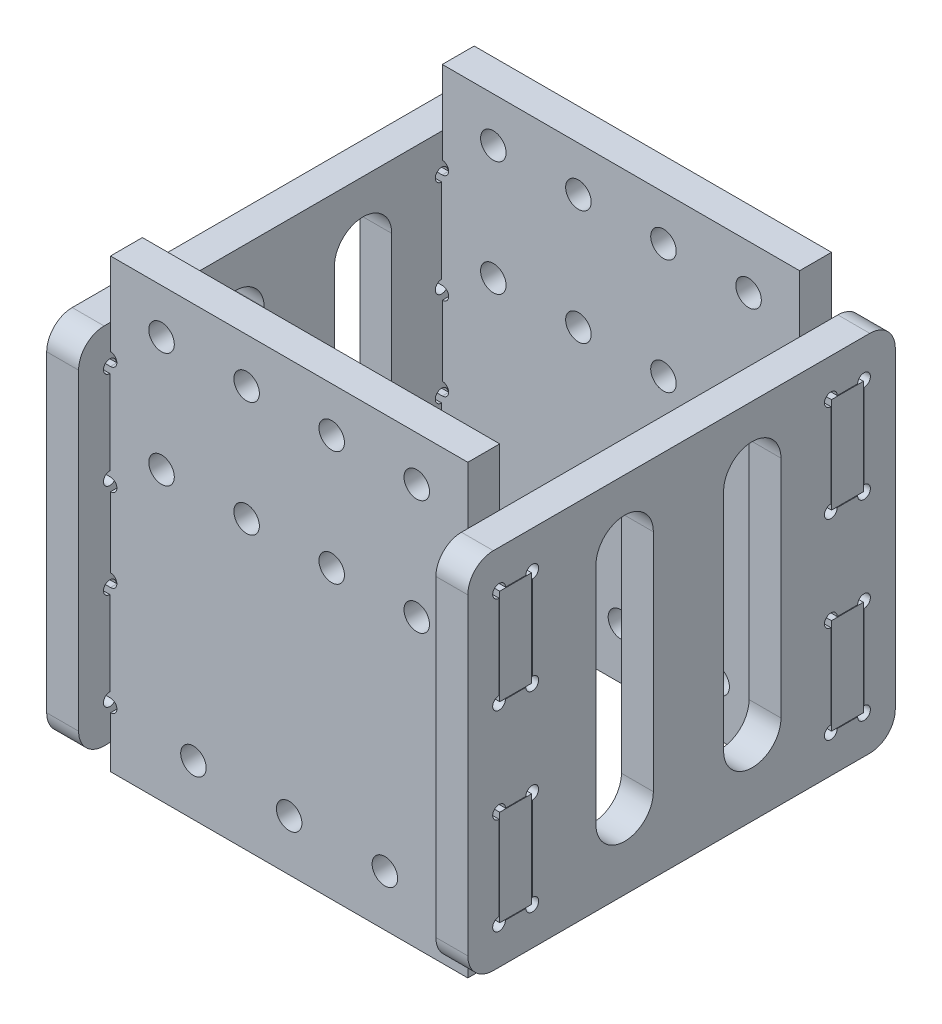
SolidWorks part; units mm, degrees
material "Thornel Mat VMA"
ref_plane "前视基准面" through (0, 0, 0) normal (0, 0, 1) x (1, 0, 0)
ref_plane "上视基准面" through (0, 0, 0) normal (0, 1, 0) x (1, 0, 0)
ref_plane "右视基准面" through (0, 0, 0) normal (1, 0, 0) x (0, 0, -1)
other "Configuration Table"
sketch "草图1" plane through (0, 0, 0) normal (0, 0, 1) x (1, 0, 0)
  line L5 (28, 35) -> (-28, 35)
  line L6 (28, 35) -> (28, 22)
  line L7 (28, -35) -> (-28, -35)
  line L8 (-28, 35) -> (-28, 22)
  line L9 (28, 35) -> (-28, -35) construction
  line L10 (28, -35) -> (-28, 35) construction
  line L11 (-28, 20) -> (-33, 20)
  line L13 (-28, 5) -> (-33, 5)
  line L14 (-33, 20) -> (-33, 5)
  line L15 (-28, 3) -> (-28, -8)
  line L16 (-28, -25) -> (-33, -25)
  line L17 (-33, -10) -> (-33, -25)
  line L18 (-28, -10) -> (-33, -10)
  line L20 (-28, -27) -> (-28, -35)
  line L21 (0, -55) -> (0, 55) construction
  line L22 (28, -25) -> (33, -25)
  line L23 (33, -10) -> (33, -25)
  line L24 (28, -10) -> (33, -10)
  line L25 (28, 5) -> (33, 5)
  line L26 (33, 20) -> (33, 5)
  line L27 (28, 20) -> (33, 20)
  line L28 (28, -25) -> (28, -35)
  line L29 (28, 3) -> (28, -8)
  circle A0 centre (-20, 28) radius 2
  circle A1 centre (-6.6667, 28) radius 2
  circle A2 centre (6.6667, 28) radius 2
  circle A3 centre (20, 28) radius 2
  circle A4 centre (-6.6667, 10) radius 2
  circle A5 centre (6.6667, 10) radius 2
  circle A6 centre (20, 10) radius 2
  circle A7 centre (-20, 10) radius 2
  circle A8 centre (-15, -27) radius 2
  circle A9 centre (0, -27) radius 2
  circle A10 centre (15, -27) radius 2
  arc A11 (-28, 3) -> (-28, 5) centre (-28, 4) ccw
  arc A12 (-28, 20) -> (-28, 22) centre (-28, 21) ccw
  arc A13 (-28, -27) -> (-28, -25) centre (-28, -26) ccw
  arc A14 (-28, -10) -> (-28, -8) centre (-28, -9) ccw
  arc A15 (28, -27) -> (28, -25) centre (28, -26) cw
  arc A16 (28, -10) -> (28, -8) centre (28, -9) cw
  arc A17 (28, 3) -> (28, 5) centre (28, 4) cw
  arc A18 (28, 20) -> (28, 22) centre (28, 21) cw
  point P0 (0, 0)
  dimension "D3" = 4
  dimension "D4" = 8
  dimension "D5" = 7
  dimension "D8" = 8
  dimension "D9" = 18
  dimension "D10" = 40
  dimension "D11" = 4
  dimension "D12" = 8
  dimension "D14" = 15
  dimension "D18" = 2
  dimension "D19" = 2
  dimension "D1" = 56
  dimension "D2" = 70
  dimension "D15" = 5
  dimension "D16" = 15
  dimension "D17" = 15
  dimension "D6" = 4
  dimension "D7" = 2
  dimension "D13" = 3
  dimension "D20" = 2
extrude "凸台-拉伸1" add sketch "草图1" along normal blind 5 contours L27 A18 L6 L5 L8 A12 L11 L14 L13 A11 L15 A14 L18 L17 L16 A13 L20 L7 L28 A15 L22 L23 L24 A16 L29 A17 L25 L26 A0 A1 A2 A3 A4 A5 A6 A7 A8 A9 A10
pattern_linear "阵列(线性)1" count 2 spacing 52 along (0, 0, -1) of bodies 106
sketch "草图2" plane through (-33, 0, 0) normal (-1, 0, 0) x (0, 0, 1)
  line L0 (-52.1, 19.1) -> (-52.1, 5.9)
  line L1 (-51.1, 4.9) -> (-47.9, 4.9)
  line L2 (-46.9, 5.9) -> (-46.9, 19.1)
  line L3 (-47.9, 20.1) -> (-51.1, 20.1)
  line L4 (-52, 20) -> (-52, 5)
  line L5 (-52, 5) -> (-47, 5)
  line L6 (-47, 5) -> (-47, 20)
  line L7 (-47, 20) -> (-52, 20)
  line L8 (-52, 20) -> (-52, 5) construction
  line L9 (-52, 5) -> (-47, 5) construction
  line L10 (-47, 5) -> (-47, 20) construction
  line L11 (-47, 20) -> (-52, 20) construction
  line L12 (-52.1, 4.9) -> (-46.9, 4.9) construction
  line L13 (-46.9, 4.9) -> (-46.9, 20.1) construction
  line L14 (-52.1, 20.1) -> (-52.1, 4.9) construction
  line L15 (-46.9, 20.1) -> (-52.1, 20.1) construction
  line L16 (-52, 35) -> (-52, 22) construction
  line L17 (-57, 26) -> (10, 26)
  line L18 (-57, 26) -> (-57, -31)
  line L19 (-57, -31) -> (10, -31)
  line L20 (10, 26) -> (10, -31)
  line L21 (5, 20) -> (5, 5) construction
  line L22 (-47, -25) -> (-52, -25) construction
  line L23 (-0.1, 19.1) -> (-0.1, 5.9)
  line L24 (0.9, 4.9) -> (4.1, 4.9)
  line L25 (5.1, 5.9) -> (5.1, 19.1)
  line L26 (4.1, 20.1) -> (0.9, 20.1)
  line L27 (0, 20) -> (0, 5) construction
  line L28 (0, 5) -> (5, 5) construction
  line L29 (5, 5) -> (5, 20) construction
  line L30 (5, 20) -> (0, 20) construction
  line L31 (-0.1, -10.9) -> (-0.1, -24.1)
  line L32 (0.9, -25.1) -> (4.1, -25.1)
  line L33 (5.1, -24.1) -> (5.1, -10.9)
  line L34 (4.1, -9.9) -> (0.9, -9.9)
  line L35 (0, -10) -> (0, -25) construction
  line L36 (0, -25) -> (5, -25) construction
  line L37 (5, -25) -> (5, -10) construction
  line L38 (5, -10) -> (0, -10) construction
  line L39 (-52.1, -10.9) -> (-52.1, -24.1)
  line L40 (-51.1, -25.1) -> (-47.9, -25.1)
  line L41 (-46.9, -24.1) -> (-46.9, -10.9)
  line L42 (-47.9, -9.9) -> (-51.1, -9.9)
  line L43 (-52, -10) -> (-52, -25) construction
  line L44 (-52, -25) -> (-47, -25) construction
  line L45 (-47, -25) -> (-47, -10) construction
  line L46 (-47, -10) -> (-52, -10) construction
  arc A0 (-46.9, 19.1) -> (-47.9, 20.1) centre (-46.9, 20.1) ccw
  arc A1 (-51.1, 20.1) -> (-52.1, 19.1) centre (-52.1, 20.1) ccw
  arc A2 (-52.1, 5.9) -> (-51.1, 4.9) centre (-52.1, 4.9) ccw
  arc A3 (-47.9, 4.9) -> (-46.9, 5.9) centre (-46.9, 4.9) ccw
  arc A4 (5.1, 19.1) -> (4.1, 20.1) centre (5.1, 20.1) ccw
  arc A5 (0.9, 20.1) -> (-0.1, 19.1) centre (-0.1, 20.1) ccw
  arc A6 (-0.1, 5.9) -> (0.9, 4.9) centre (-0.1, 4.9) ccw
  arc A7 (4.1, 4.9) -> (5.1, 5.9) centre (5.1, 4.9) ccw
  arc A8 (5.1, -10.9) -> (4.1, -9.9) centre (5.1, -9.9) ccw
  arc A9 (0.9, -9.9) -> (-0.1, -10.9) centre (-0.1, -9.9) ccw
  arc A10 (-0.1, -24.1) -> (0.9, -25.1) centre (-0.1, -25.1) ccw
  arc A11 (4.1, -25.1) -> (5.1, -24.1) centre (5.1, -25.1) ccw
  arc A12 (-46.9, -10.9) -> (-47.9, -9.9) centre (-46.9, -9.9) ccw
  arc A13 (-51.1, -9.9) -> (-52.1, -10.9) centre (-52.1, -9.9) ccw
  arc A14 (-52.1, -24.1) -> (-51.1, -25.1) centre (-52.1, -25.1) ccw
  arc A15 (-47.9, -25.1) -> (-46.9, -24.1) centre (-46.9, -25.1) ccw
  dimension "D3" = 2
  dimension "D4" = 2
  dimension "D5" = 2
  dimension "D6" = 2
  dimension "D7" = 6
  dimension "D8" = 5
  dimension "D9" = 5
  dimension "D10" = 6
  dimension "D1" = 0
  dimension "D2" = 0.1
  dimension "D11" = 2
  dimension "D12" = 2
extrude "凸台-拉伸2" add sketch "草图2" against normal blind 5 separate body
fillet "圆角1" radius 4 4 edges at (-30.5, 26, 10) (-30.5, -31, 10) (-30.5, -31, -57) (-30.5, 26, -57)
sketch "草图3" plane through (-33, 0, 0) normal (-1, 0, 0) x (0, 0, 1)
  line L0 (-34.5838, 16.0265) -> (-34.5838, -19.2468) construction
  line L1 (-30.0904, 16.0265) -> (-30.0904, -19.2468)
  line L2 (-39.0772, 16.0265) -> (-39.0772, -19.2468)
  line L3 (-14.5838, 16.0265) -> (-14.5838, -19.2468) construction
  line L4 (-10.0904, 16.0265) -> (-10.0904, -19.2468)
  line L5 (-19.0772, 16.0265) -> (-19.0772, -19.2468)
  arc A0 (-30.0904, 16.0265) -> (-39.0772, 16.0265) centre (-34.5838, 16.0265) ccw
  arc A1 (-39.0772, -19.2468) -> (-30.0904, -19.2468) centre (-34.5838, -19.2468) ccw
  arc A2 (-10.0904, 16.0265) -> (-19.0772, 16.0265) centre (-14.5838, 16.0265) ccw
  arc A3 (-19.0772, -19.2468) -> (-10.0904, -19.2468) centre (-14.5838, -19.2468) ccw
  point P2 (-34.5838, -1.6101)
  point P10 (-14.5838, -1.6101)
  dimension "D1" = 2
extrude "切除-拉伸1" cut sketch "草图3" against normal blind 5
pattern_linear "阵列(线性)2" count 2 spacing 61 along (1, 0, 0) of bodies 109
